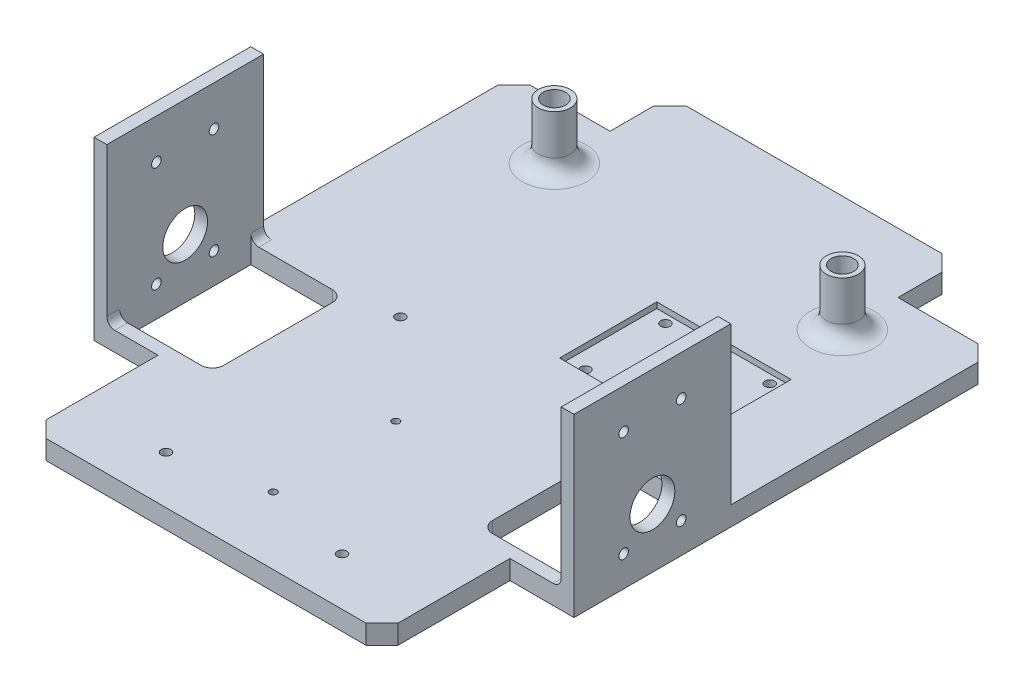
SolidWorks part; units mm, degrees
ref_plane "Front Plane" through (0, 0, 0) normal (0, 0, 1) x (1, 0, 0)
ref_plane "Top Plane" through (0, 0, 0) normal (0, 1, 0) x (1, 0, 0)
ref_plane "Right Plane" through (0, 0, 0) normal (1, 0, 0) x (0, 0, -1)
sketch "Sketch1" plane through (0, 0, 0) normal (0, 1, 0) x (1, 0, 0)
  line L1 (-75, 95) -> (75, 95)
  line L2 (-75, 95) -> (-75, -95)
  line L3 (-75, -95) -> (75, -95)
  line L4 (75, 95) -> (75, -95)
  line L5 (-75, 95) -> (75, -95) construction
  line L6 (-75, -95) -> (75, 95) construction
  point P0 (0, 0)
  dimension "D1" = 190
  dimension "D2" = 150
extrude "Boss-Extrude1" add sketch "Sketch1" along normal blind 6
sketch "Sketch2" plane through (0, 6, 0) normal (0, 1, 0) x (1, 0, 0)
  line L0 (-75, 76.25) -> (75, 76.25) construction
  line L1 (-75, 95) -> (-75, -95) construction
  line L2 (75, -95) -> (75, 95) construction
  line L3 (75, 95) -> (-75, 95) construction
  line L4 (-45, 95) -> (-45, 76.25) construction
  line L5 (45, 76.25) -> (45, 95) construction
  line L7 (-45, 76.25) -> (-75, 76.25)
  line L8 (-45, 76.25) -> (-45, 95)
  line L9 (-45, 95) -> (-75, 95)
  line L10 (-75, 76.25) -> (-75, 95)
  line L11 (45, 95) -> (75, 95)
  line L12 (45, 95) -> (45, 76.25)
  line L13 (45, 76.25) -> (75, 76.25)
  line L14 (75, 95) -> (75, 76.25)
  dimension "D1" = 18.75
  dimension "D2" = 30
  dimension "D3" = 30
extrude "Cut-Extrude1" cut sketch "Sketch2" against normal blind 6
chamfer "Chamfer1" distance 5 angle 45 4 edges at (75, 3, -76.25) (45, 3, -95) (-75, 3, -76.25) (-45, 3, -95)
sketch "Sketch3" plane through (0, 6, 0) normal (0, 1, 0) x (1, 0, 0)
  line L1 (-75, -95) -> (-55, -95)
  line L2 (-75, -95) -> (-75, -55)
  line L3 (-75, -55) -> (-55, -55)
  line L4 (-55, -95) -> (-55, -55)
  line L5 (75, -95) -> (55, -95)
  line L6 (75, -95) -> (75, -55)
  line L7 (75, -55) -> (55, -55)
  line L8 (55, -95) -> (55, -55)
  dimension "D1" = 40
  dimension "D2" = 20
  dimension "D3" = 20
extrude "Cut-Extrude2" cut sketch "Sketch3" against normal blind 6
sketch "Sketch5" plane through (0, 6, 0) normal (0, 1, 0) x (1, 0, 0)
  line L0 (0, -95) -> (0, 22.318) construction
  line L1 (-55, -95) -> (55, -95) construction
  line L2 (-49.9317, -83) -> (49.077, -83) construction
  line L3 (-45, -83) -> (-45, 22.318) construction
  line L4 (45, -83) -> (45, 22.318) construction
  line L5 (-37.75, -83) -> (-37.75, -21.8) construction
  line L6 (37.75, -83) -> (37.75, -21.8) construction
  line L7 (-37.75, -21.8) -> (37.75, -21.8) construction
  circle A0 centre (0, -74) radius 1.125
  circle A1 centre (0, -35.7) radius 1.125
  dimension "D7" = 9
  dimension "D8" = 38.3
  dimension "D1" = 12
  dimension "D2" = 45
  dimension "D3" = 45
  dimension "D4" = 61.2
  dimension "D5" = 7.25
  dimension "D6" = 7.25
extrude "Cut-Extrude4" cut sketch "Sketch5" against normal blind 3.75
sketch "Sketch9" plane through (0, 6, 0) normal (0, 1, 0) x (1, 0, 0)
  line L0 (-75, 58.865) -> (75, 58.865) construction
  line L1 (-75, 71.25) -> (-75, -55) construction
  line L2 (75, -55) -> (75, 71.25) construction
  line L3 (-45, 76.25) -> (-45, 58.865) construction
  line L4 (45, 76.25) -> (45, 58.865) construction
  circle A1 centre (-45, 58.865) radius 5
  circle A2 centre (45, 58.865) radius 5
extrude "Pole supports" add sketch "Sketch9" along normal blind 17.5
fillet "Fillet1" radius 5 2 edges at (45, 6, -53.865) (-45, 6, -53.865)
sketch "Sketch10" plane through (0, 23.5, 0) normal (0, 1, 0) x (1, 0, 0)
  circle A0 centre (-45, 58.865) radius 3.5
extrude "Pole support hole - left" cut sketch "Sketch10" against normal blind 17.5
sketch "Sketch11" plane through (0, 23.5, 0) normal (0, 1, 0) x (1, 0, 0)
  circle A0 centre (45, 58.865) radius 3.5
extrude "Pole support hole - right" cut sketch "Sketch11" against normal blind 17.5
sketch "Sketch12" plane through (0, 6, 0) normal (0, 1, 0) x (1, 0, 0)
  circle A0 centre (-45, 58.865) radius 2
  circle A1 centre (45, 58.865) radius 2
extrude "Pole support screw" cut sketch "Sketch12" against normal blind 6
sketch "Sketch13" plane through (0, 6, 0) normal (0, 1, 0) x (1, 0, 0)
  line L0 (-75, 22.18) -> (75, 22.18) construction
  line L1 (-75, 71.25) -> (-75, -55) construction
  line L2 (75, -55) -> (75, 71.25) construction
  line L3 (40, 95) -> (-40, 95) construction
  line L4 (8.5, -13.3309) -> (8.5, 95) construction
  line L5 (8.5, 37.38) -> (50.5, 37.38) construction
  line L6 (8.5, 6.98) -> (50.5, 6.98) construction
  line L8 (50.5, 37.38) -> (8.5, 37.38)
  line L9 (50.5, 37.38) -> (50.5, 6.98)
  line L10 (50.5, 6.98) -> (8.5, 6.98)
  line L11 (8.5, 37.38) -> (8.5, 6.98)
  dimension "D1" = 72.82
  dimension "D2" = 66.5
  dimension "D3" = 15.2
  dimension "D4" = 42
  dimension "D5" = 15.2
extrude "Pulley mount" cut sketch "Sketch13" against normal blind 1.8
sketch "Sketch15" plane through (0, 4.2, 0) normal (0, 1, 0) x (1, 0, 0)
  line L0 (8.5, 37.38) -> (8.5, 6.98) construction
  line L1 (50.5, 37.38) -> (8.5, 37.38) construction
  line L2 (50.5, 6.98) -> (50.5, 37.38) construction
  line L3 (8.5, 6.98) -> (50.5, 6.98) construction
  circle A0 centre (13.9, 34.68) radius 1.5
  circle A1 centre (46.5, 34.68) radius 1.5
  circle A2 centre (46.5, 9.68) radius 1.5
  circle A3 centre (13.9, 9.68) radius 1.5
  dimension "D1" = 5.4
  dimension "D3" = 4
  dimension "D4" = 2.7
  dimension "D5" = 5.4
  dimension "D2" = 2.7
extrude "Pulley mount screws" cut sketch "Sketch15" against normal blind 4.7
sketch "Sketch16" plane through (0, 6, 0) normal (0, 1, 0) x (1, 0, 0)
  line L1 (-75, -55) -> (-71, -55)
  line L2 (-75, -55) -> (-75, -6)
  line L3 (-75, -6) -> (-71, -6)
  line L4 (-71, -55) -> (-71, -6)
  line L5 (75, -55) -> (71, -55)
  line L6 (75, -55) -> (75, -6)
  line L7 (75, -6) -> (71, -6)
  line L8 (71, -55) -> (71, -6)
  dimension "D1" = 4
  dimension "D2" = 49
  dimension "D3" = 4
  dimension "D4" = 49
extrude "Motor mounts" add sketch "Sketch16" along normal blind 49
sketch "Sketch17" plane through (-71, 0, 0) normal (1, 0, 0) x (0, 0, -1)
  line L0 (-30.5, 55) -> (-30.5, 6) construction
  line L1 (-55, 55) -> (-6, 55) construction
  line L2 (-55, 6) -> (-6, 6) construction
  line L3 (-46.5, 55) -> (-46.5, 6) construction
  line L4 (-14.5, 55) -> (-14.5, 6) construction
  line L5 (-46.5, 53.5) -> (-14.5, 53.5) construction
  line L6 (-55, 30.5) -> (-6, 30.5) construction
  line L7 (-55, 55) -> (-55, 6) construction
  line L8 (-6, 55) -> (-6, 6) construction
  line L9 (-46.5, 7.5) -> (-14.5, 7.5) construction
  circle A0 centre (-30.5, 18.5) radius 7
  circle A1 centre (-39.5, 9.5) radius 1.5
  circle A2 centre (-21.5, 9.5) radius 1.5
  circle A3 centre (-39.5, 42.5) radius 1.5
  circle A4 centre (-21.5, 42.5) radius 1.5
  dimension "D5" = 14
  dimension "D7" = 9
  dimension "D9" = 7
  dimension "D10" = 33
  dimension "D1" = 16
  dimension "D2" = 16
  dimension "D3" = 23
  dimension "D4" = 23
  dimension "D6" = 11
  dimension "D8" = 7
extrude "Motor mounting holes - left" cut sketch "Sketch17" against normal blind 4
sketch "Sketch18" plane through (0, 6, 0) normal (0, 1, 0) x (1, 0, 0)
  line L0 (-42, -55) -> (-42, -5.4856) construction
  line L1 (-55, -55) -> (-71, -55) construction
  line L2 (-71, -55) -> (-71, -6) construction
  line L3 (-71, -30.5) -> (-42, -30.5) construction
  line L4 (-42, -51) -> (-71, -51) construction
  line L6 (-71, -51) -> (-42, -51)
  line L7 (-71, -51) -> (-71, -10)
  line L8 (-71, -10) -> (-42, -10)
  line L9 (-42, -51) -> (-42, -10)
  dimension "D1" = 29
  dimension "D2" = 20.5
  dimension "D3" = 41
extrude "Motor cutout - left" cut sketch "Sketch18" against normal blind 6.5
fillet "Fillet2" radius 2.5 2 edges at (-71, 6, 8) (-71, 6, 53)
sketch "Sketch20" plane through (71, 0, 0) normal (-1, 0, 0) x (0, 0, 1)
  line L0 (6, 30.5) -> (55, 30.5) construction
  line L1 (6, 55) -> (6, 6) construction
  line L2 (55, 55) -> (55, 6) construction
  line L3 (14.5, 55) -> (14.5, 6) construction
  line L4 (6, 55) -> (55, 55) construction
  line L5 (6, 6) -> (55, 6) construction
  line L6 (30.5, 55) -> (30.5, 6) construction
  line L7 (46.5, 55) -> (46.5, 6) construction
  line L8 (14.5, 53.5) -> (46.5, 53.5) construction
  line L9 (14.5, 7.5) -> (46.5, 7.5) construction
  circle A0 centre (30.5, 18.5) radius 7
  circle A1 centre (21.5, 9.5) radius 1.5
  circle A2 centre (39.5, 9.5) radius 1.5
  circle A3 centre (21.5, 42.5) radius 1.5
  circle A4 centre (39.5, 42.5) radius 1.5
  dimension "D5" = 14
  dimension "D7" = 7
  dimension "D9" = 7
  dimension "D10" = 33
  dimension "D1" = 16
  dimension "D2" = 16
  dimension "D3" = 23
  dimension "D4" = 23
  dimension "D6" = 11
  dimension "D8" = 9
extrude "Motor mounting holes - right" cut sketch "Sketch20" against normal blind 4
sketch "Sketch21" plane through (0, 6, 0) normal (0, 1, 0) x (1, 0, 0)
  line L0 (42, -57.1453) -> (42, -1.6264) construction
  line L1 (71, -6) -> (71, -55) construction
  line L2 (71, -30.5) -> (42, -30.5) construction
  line L3 (71, -10) -> (42, -10) construction
  line L5 (71, -10) -> (42, -10)
  line L6 (71, -10) -> (71, -51)
  line L7 (71, -51) -> (42, -51)
  line L8 (42, -10) -> (42, -51)
  dimension "D1" = 29
  dimension "D2" = 20.5
  dimension "D3" = 41
extrude "Motor cutout - right" cut sketch "Sketch21" against normal blind 6
fillet "Fillet3" radius 2.5 2 edges at (71, 6, 53) (71, 6, 8)
sketch "Sketch23" plane through (0, 6, 0) normal (0, 1, 0) x (1, 0, 0)
  line L0 (-55, -83) -> (55, -83) construction
  line L1 (-55, -95) -> (-55, -55) construction
  line L2 (55, -55) -> (55, -95) construction
  line L3 (-55, -95) -> (55, -95) construction
  line L4 (0, -95) -> (0, -34) construction
  line L5 (0, -88.755) -> (-30.5, -88.755) construction
  line L6 (0, -88.755) -> (30.5, -88.755) construction
  line L7 (-30.5, -88.755) -> (-30.5, -3.755) construction
  line L8 (-30.5, -3.755) -> (30.5, -3.755) construction
  line L9 (30.5, -3.755) -> (30.5, -88.755) construction
  circle A3 centre (-27.5, -6.755) radius 1.5
  circle A4 centre (27.5, -6.755) radius 1.5
  circle A5 centre (-27.5, -80) radius 1.5
  circle A6 centre (27.5, -80) radius 1.5
  dimension "D3" = 30.5
  dimension "D4" = 30.5
  dimension "D5" = 85
  dimension "D6" = 3
  dimension "D8" = 3
  dimension "D9" = 3
  dimension "D1" = 12
  dimension "D2" = 61
  dimension "D7" = 3
extrude "Arduino mounting holes" cut sketch "Sketch23" against normal blind 6
sketch "Sketch24" plane through (0, 0, 0) normal (0, -1, 0) x (1, 0, 0)
  circle A0 centre (45, -58.865) radius 4
  circle A1 centre (-45, -58.865) radius 4
extrude "Cut-Extrude20" cut sketch "Sketch24" against normal blind 2
chamfer "Chamfer2" distance 5 angle 45 2 edges at (55, 3, 95) (-55, 3, 95)
fillet "Fillet4" radius 3.5 4 edges at (42, 3, 51) (42, 3, 10) (-42, 3, 51) (-42, 3, 10)
